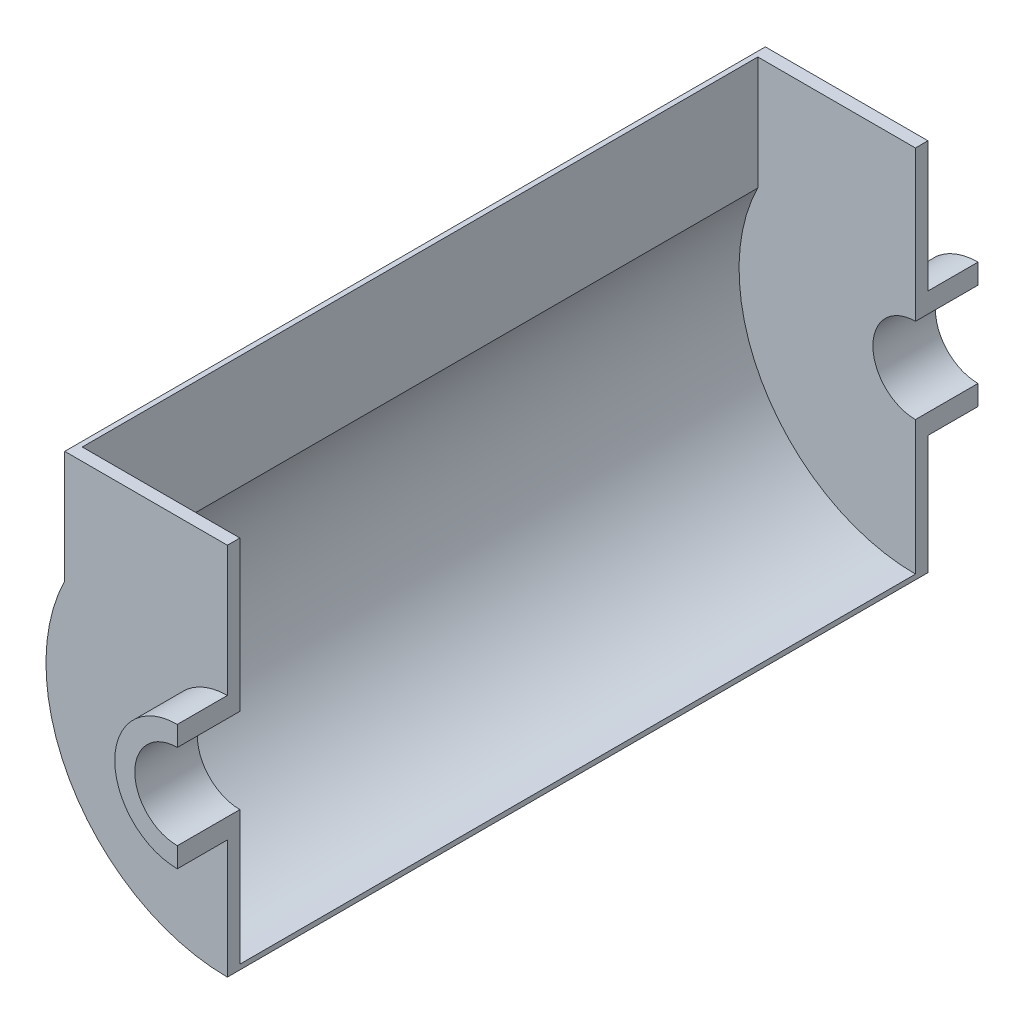
SolidWorks part; units mm, degrees
ref_plane "Front Plane" through (0, 0, 0) normal (0, 0, 1) x (1, 0, 0)
ref_plane "Top Plane" through (0, 0, 0) normal (0, 1, 0) x (1, 0, 0)
ref_plane "Right Plane" through (0, 0, 0) normal (1, 0, 0) x (0, 0, -1)
sketch "Sketch1" plane through (0, 0, 0) normal (0, 0, 1) x (1, 0, 0)
  line L0 (0, 25) -> (0, 17)
  line L1 (0, -17) -> (0, -25)
  arc A0 (0, 25) -> (0, -25) centre (0, 0) ccw
  arc A1 (0, 17) -> (0, -17) centre (0, 0) ccw
  dimension "D1" = 34
  dimension "D2" = 50
extrude "Boss-Extrude1" add sketch "Sketch1" along normal blind 20 and the other way blind 5
sketch "Sketch2" plane through (0, 0, 0) normal (0, 0, 1) x (1, 0, 0)
  line L0 (0, 25) -> (0, 77)
  line L1 (0, 77) -> (-65, 77)
  line L2 (-65, 77) -> (-65, 32.1131)
  line L3 (0, -25) -> (0, -72.5)
  arc A0 (-65, 32.1131) -> (0, -72.5) centre (0, 0) ccw
  arc A1 (0, 25) -> (0, -25) centre (0, 0) ccw construction
  arc A2 (0, 25) -> (0, -25) centre (0, 0) ccw
  dimension "D3" = 72.5
  dimension "D1" = 52
  dimension "D2" = 65
extrude "Boss-Extrude2" add sketch "Sketch2" against normal blind 5
ref_plane "Plane1" through (0, 0, -140) normal (0, 0, 1) x (1, 0, 0)
mirror "Mirror1" about plane through (0, 0, -140) normal (0, 0, 1) of bodies 102
sketch "Sketch3" plane through (0, 0, -5) normal (0, 0, -1) x (-1, 0, 0)
  line L0 (63, 31.6425) -> (63, 77)
  line L1 (0, -70.5) -> (0, -72.5)
  line L2 (63, 77) -> (65, 77)
  line L4 (0, -17) -> (0, -72.5)
  line L5 (65, 32.1131) -> (65, 77)
  line L6 (65, 77) -> (0, 77)
  line L7 (0, 77) -> (0, 17)
  line L9 (65, 32.1131) -> (65, 77)
  line L10 (65, 77) -> (0, 77)
  arc A0 (0, -70.5) -> (63, 31.6425) centre (0, 0) ccw
  arc A2 (0, -17) -> (0, 17) centre (0, 0) ccw
  arc A3 (0, -72.5) -> (65, 32.1131) centre (0, 0) ccw
  arc A5 (0, -72.5) -> (65, 32.1131) centre (0, 0) ccw
  dimension "D1" = 0
  dimension "D2" = 2
extrude "Boss-Extrude4" add sketch "Sketch3" along normal up to body contours L9 A5 L1 A0 L0 L2
